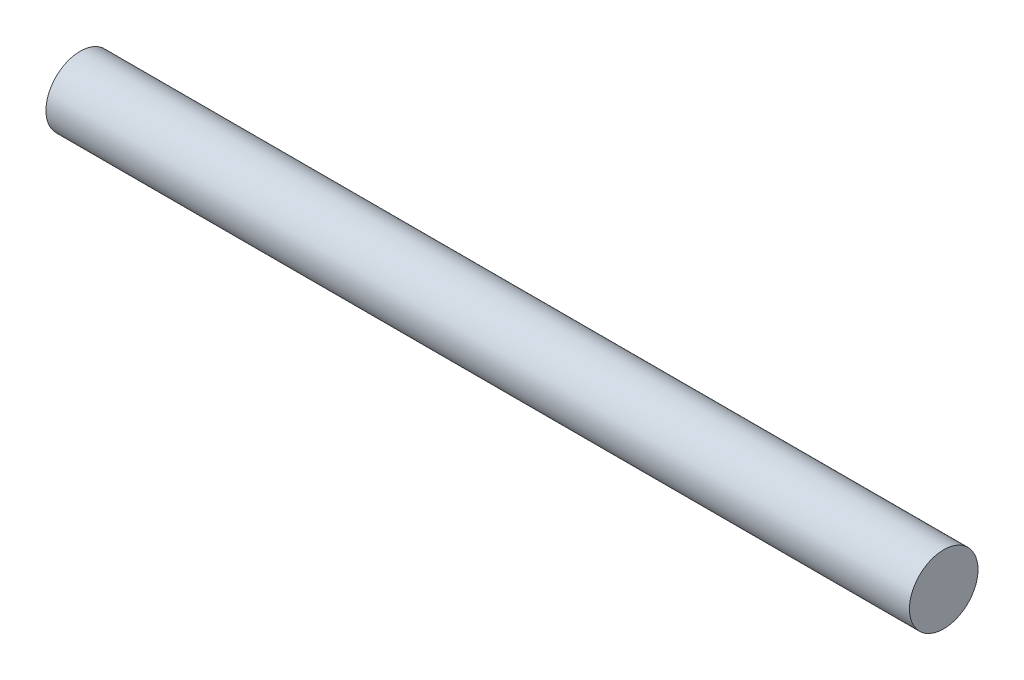
SolidWorks part; units mm, degrees
material "6061 Alloy"
ref_plane "Front Plane" through (0, 0, 0) normal (0, 0, 1) x (1, 0, 0)
ref_plane "Top Plane" through (0, 0, 0) normal (0, 1, 0) x (1, 0, 0)
ref_plane "Right Plane" through (0, 0, 0) normal (1, 0, 0) x (0, 0, -1)
sketch "Sketch1" plane through (0, 0, 0) normal (1, 0, 0) x (0, 0, -1)
  circle A0 centre (0, 0) radius 2.5
  dimension "D1" = 5
extrude "Boss-Extrude1" add sketch "Sketch1" along normal blind 62.95
